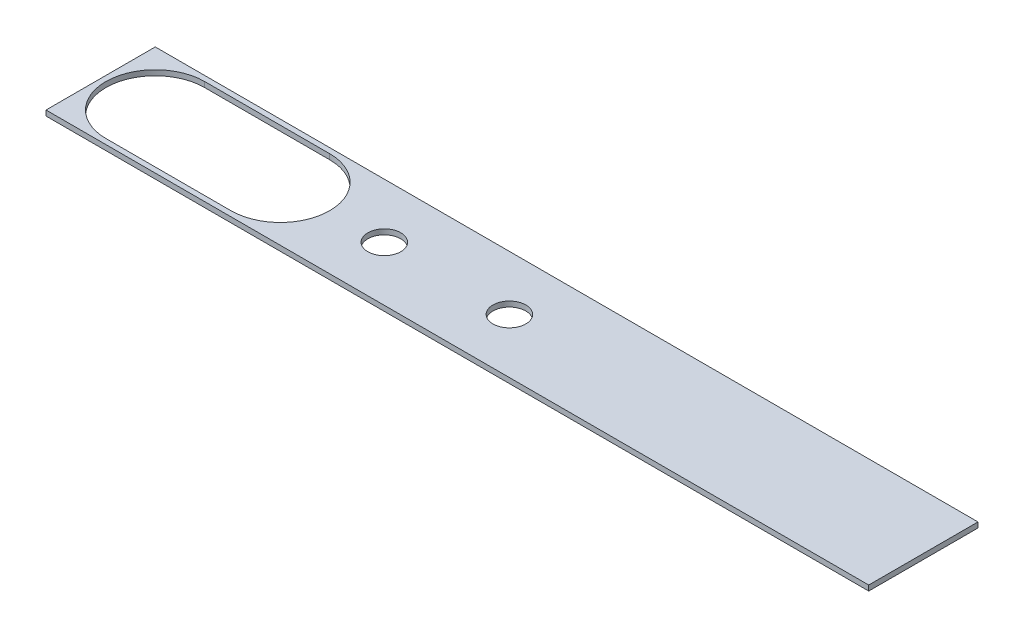
SolidWorks part; units mm, degrees
material "AISI 1020 Steel, Cold Rolled"
ref_plane "Front Plane" through (0, 0, 0) normal (0, 0, 1) x (1, 0, 0)
ref_plane "Top Plane" through (0, 0, 0) normal (0, 1, 0) x (1, 0, 0)
ref_plane "Right Plane" through (0, 0, 0) normal (1, 0, 0) x (0, 0, -1)
sketch "Sketch1" plane through (0, 0, 0) normal (0, 1, 0) x (1, 0, 0)
  line L1 (-125, 16.6) -> (125, 16.6)
  line L2 (-125, 16.6) -> (-125, -16.6)
  line L3 (-125, -16.6) -> (125, -16.6)
  line L4 (125, 16.6) -> (125, -16.6)
  line L5 (-125, 16.6) -> (125, -16.6) construction
  line L6 (-125, -16.6) -> (125, 16.6) construction
  point P0 (0, 0)
  dimension "D1" = 250
  dimension "D2" = 33.2
extrude "Boss-Extrude1" add sketch "Sketch1" against normal blind 1.6
sketch "Sketch2" plane through (0, 0, 0) normal (0, 1, 0) x (1, 0, 0)
  line L0 (-123.4, 16.6) -> (-123.4, -16.6) construction
  line L1 (125, 16.6) -> (-125, 16.6) construction
  line L2 (-125, -16.6) -> (125, -16.6) construction
  line L3 (-55.4, 16.6) -> (-55.4, -16.6) construction
  line L4 (-53.8, 16.6) -> (-53.8, -16.6) construction
  line L5 (14.2, 16.6) -> (14.2, -16.6) construction
  line L6 (-125, 16.6) -> (-125, -16.6) construction
  line L7 (-123.4, 0) -> (14.2, 0) construction
  line L8 (-108.4, 15) -> (-70.4, 15)
  line L9 (-108.4, -15) -> (-70.4, -15)
  line L10 (-38.8, -15) -> (-0.8, -15) construction
  line L11 (-38.8, 15) -> (-0.8, 15) construction
  arc A0 (-108.4, 15) -> (-108.4, -15) centre (-108.4, 0) ccw
  arc A1 (-70.4, -15) -> (-70.4, 15) centre (-70.4, 0) ccw
  circle A2 centre (-38.8, 0) radius 5
  circle A3 centre (-0.8, 0) radius 5
  arc A4 (-0.8, -15) -> (-0.8, 15) centre (-0.8, 0) ccw construction
  arc A5 (-38.8, 15) -> (-38.8, -15) centre (-38.8, 0) ccw construction
  dimension "D5" = 15
  dimension "D8" = 10
  dimension "D1" = 1.6
  dimension "D2" = 68
  dimension "D3" = 1.6
  dimension "D4" = 68
  dimension "D6" = 15
  dimension "D7" = 15
  dimension "D9" = 137.6
  dimension "D10" = 2
extrude "Cut-Extrude1" cut sketch "Sketch2" against normal through all
